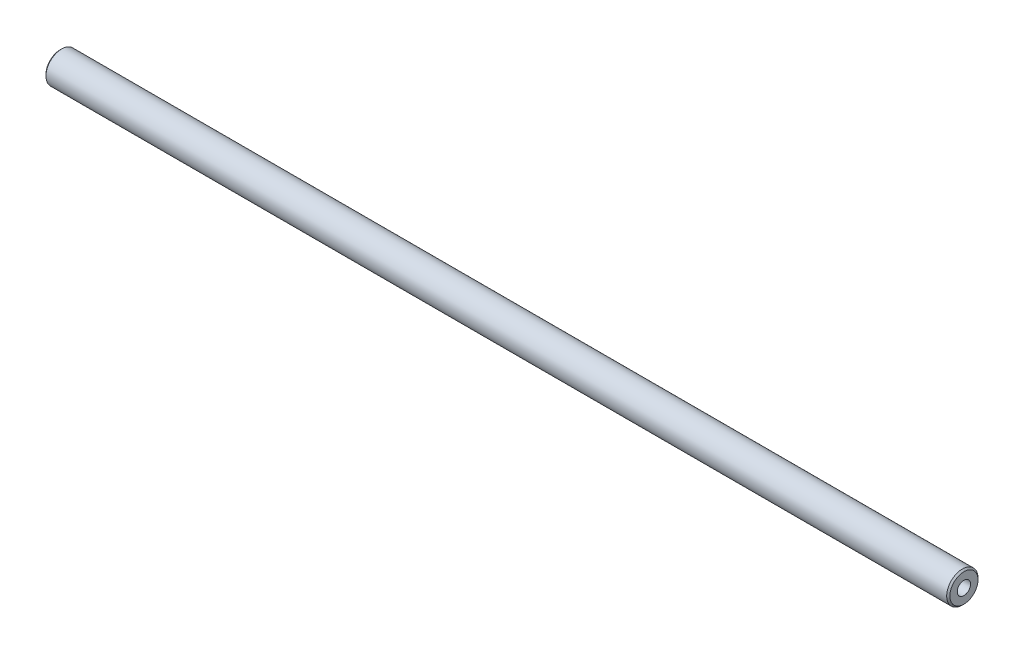
SolidWorks part; units mm, degrees
ref_plane "前视基准面" through (0, 0, 0) normal (0, 0, 1) x (1, 0, 0)
ref_plane "上视基准面" through (0, 0, 0) normal (0, 1, 0) x (1, 0, 0)
ref_plane "右视基准面" through (0, 0, 0) normal (1, 0, 0) x (0, 0, -1)
sketch "草图1" plane through (0, 0, 0) normal (1, 0, 0) x (0, 0, -1)
  circle A0 centre (0, 0) radius 10
  dimension "D1" = 20
extrude "凸台-拉伸1" add sketch "草图1" along normal mid plane 577.5
hole_wizard "M10x1.5 螺纹孔1" positions "草图3" profile "草图2" tap size "M10x1.5" standard "JIS"
sketch "草图3" plane through (288.75, 0, 0) normal (1, 0, 0) x (0, 0, -1)
  point P1 (0, 0)
sketch "草图2" plane through (288.75, 0, 0) normal (0, 1, 0) x (0, 0, -1)
  line L0 (0, 0) -> (0, 27.0537)
  line L1 (0, 27.0537) -> (4.25, 24.5)
  line L2 (4.25, 24.5) -> (4.25, 0)
  line L5 (4.25, 0) -> (0, 0)
  line L10 (0, 27.0537) -> (-4.25, 24.5) construction
  line L11 (0, -6.35) -> (0, 107.95) construction
  dimension "螺纹孔钻头直径" = 8.5
  dimension "螺纹孔钻头深度" = 24.5
  dimension "导头角度" = 118
cosmetic thread "孔螺蚊线1" parameters "D1"=20, "D2"=10
chamfer "倒角1" distance 1 angle 45 2 edges at (288.75, 0, -10) (-288.75, 0, -10)
